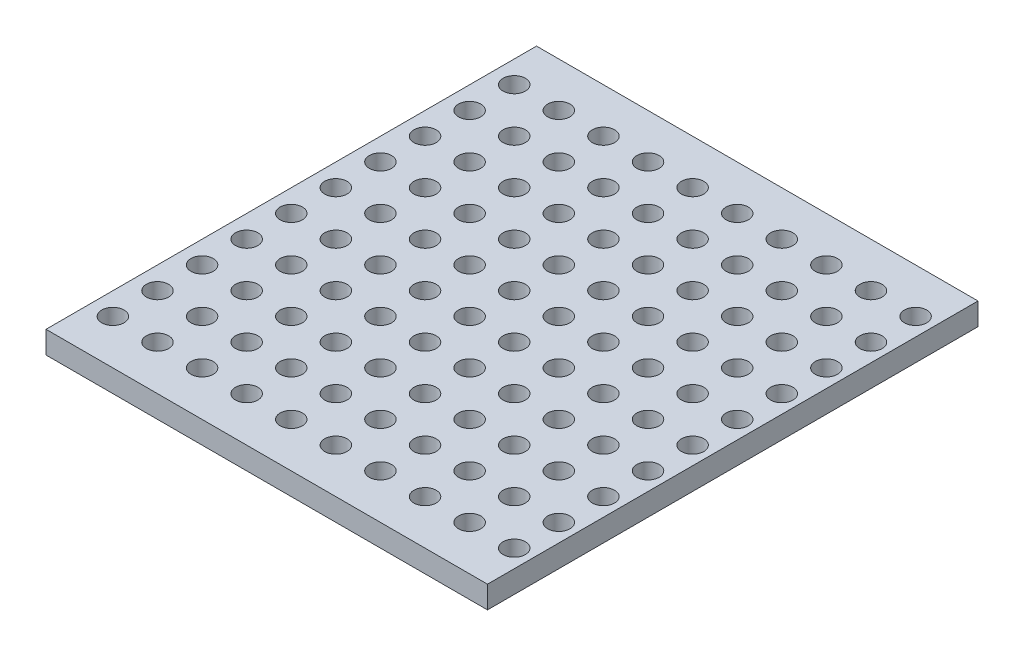
SolidWorks part; units mm, degrees
ref_plane "Alzado" through (0, 0, 0) normal (0, 0, 1) x (1, 0, 0)
ref_plane "Planta" through (0, 0, 0) normal (0, 1, 0) x (1, 0, 0)
ref_plane "Vista lateral" through (0, 0, 0) normal (1, 0, 0) x (0, 0, -1)
sketch "Croquis1" plane through (0, 0, 0) normal (0, 1, 0) x (1, 0, 0)
  line L1 (-9.9, 11) -> (9.9, 11)
  line L2 (-9.9, 11) -> (-9.9, -11)
  line L3 (-9.9, -11) -> (9.9, -11)
  line L4 (9.9, 11) -> (9.9, -11)
  line L5 (-9.9, 11) -> (9.9, -11) construction
  line L6 (-9.9, -11) -> (9.9, 11) construction
  point P0 (0, 0)
  dimension "D1" = 19.8
  dimension "D2" = 22
extrude "Saliente-Extruir1" add sketch "Croquis1" along normal blind 1
sketch "Croquis2" plane through (0, 1, 0) normal (0, 1, 0) x (1, 0, 0)
  line L0 (-9.9, 11) -> (-9.9, -11) construction
  line L1 (9.9, 11) -> (-9.9, 11) construction
  point P0 (-8.9, 9)
  point P3 (-6.9, 9)
  point P6 (-4.9, 9)
  point P7 (-0.9, 9)
  point P8 (1.1, 9)
  point P9 (3.1, 9)
  point P10 (5.1, 9)
  point P11 (7.1, 9)
  point P12 (9.1, 9)
  point P13 (-2.9, 9)
  point P14 (-8.9, 7)
  point P15 (-6.9, 7)
  point P16 (-4.9, 7)
  point P17 (-2.9, 7)
  point P18 (-0.9, 7)
  point P19 (1.1, 7)
  point P20 (3.1, 7)
  point P21 (5.1, 7)
  point P22 (7.1, 7)
  point P23 (9.1, 7)
  point P24 (-8.9, 5)
  point P25 (-6.9, 5)
  point P26 (-4.9, 5)
  point P27 (-2.9, 5)
  point P28 (-0.9, 5)
  point P29 (1.1, 5)
  point P30 (3.1, 5)
  point P31 (5.1, 5)
  point P32 (7.1, 5)
  point P33 (9.1, 5)
  point P34 (-8.9, 3)
  point P35 (-6.9, 3)
  point P36 (-4.9, 3)
  point P37 (-2.9, 3)
  point P38 (-0.9, 3)
  point P39 (1.1, 3)
  point P40 (3.1, 3)
  point P41 (5.1, 3)
  point P42 (7.1, 3)
  point P43 (9.1, 3)
  point P44 (-8.9, 1)
  point P45 (-6.9, 1)
  point P46 (-4.9, 1)
  point P47 (-2.9, 1)
  point P48 (-0.9, 1)
  point P49 (1.1, 1)
  point P50 (3.1, 1)
  point P51 (5.1, 1)
  point P52 (7.1, 1)
  point P53 (9.1, 1)
  point P54 (-8.9, -1)
  point P55 (-6.9, -1)
  point P56 (-4.9, -1)
  point P57 (-2.9, -1)
  point P58 (-0.9, -1)
  point P59 (1.1, -1)
  point P60 (3.1, -1)
  point P61 (5.1, -1)
  point P62 (7.1, -1)
  point P63 (9.1, -1)
  point P64 (-8.9, -3)
  point P65 (-6.9, -3)
  point P66 (-4.9, -3)
  point P67 (-2.9, -3)
  point P68 (-0.9, -3)
  point P69 (1.1, -3)
  point P70 (3.1, -3)
  point P71 (5.1, -3)
  point P72 (7.1, -3)
  point P73 (9.1, -3)
  point P74 (-8.9, -5)
  point P75 (-6.9, -5)
  point P76 (-4.9, -5)
  point P77 (-2.9, -5)
  point P78 (-0.9, -5)
  point P79 (1.1, -5)
  point P80 (3.1, -5)
  point P81 (5.1, -5)
  point P82 (7.1, -5)
  point P83 (9.1, -5)
  point P84 (-8.9, -7)
  point P85 (-6.9, -7)
  point P86 (-4.9, -7)
  point P87 (-2.9, -7)
  point P88 (-0.9, -7)
  point P89 (1.1, -7)
  point P90 (3.1, -7)
  point P91 (5.1, -7)
  point P92 (7.1, -7)
  point P93 (9.1, -7)
  point P94 (-8.9, -9)
  point P95 (-6.9, -9)
  point P96 (-4.9, -9)
  point P97 (-2.9, -9)
  point P98 (-0.9, -9)
  point P99 (1.1, -9)
  point P100 (3.1, -9)
  point P101 (5.1, -9)
  point P102 (7.1, -9)
  point P103 (9.1, -9)
  dimension "D1" = 1
  dimension "D2" = 2
  dimension "D3" = 2
  dimension "D4" = 2
  dimension "D5" = 2
  dimension "D6" = 2
  dimension "D7" = 2
  dimension "D8" = 2
  dimension "D9" = 2
  dimension "D10" = 2
  dimension "D11" = 2
  dimension "D12" = 2
  dimension "D13" = 2
  dimension "D14" = 2
  dimension "D15" = 2
  dimension "D16" = 2
  dimension "D17" = 2
  dimension "D18" = 2
  dimension "D19" = 2
  dimension "D20" = 2
hole_wizard "Diámetro de taladro Ø1.0 (1)1" positions "Croquis3D2" profile "Croquis3" hole size "Ø1.0" standard "DIN"
sketch3d "Croquis3D2"
  point P0 (-8.9, 1, -9)
  point P3 (-6.9, 1, -9)
  point P6 (-4.9, 1, -9)
  point P9 (-2.9, 1, -9)
  point P12 (-0.9, 1, -9)
  point P15 (1.1, 1, -9)
  point P18 (3.1, 1, -9)
  point P21 (5.1, 1, -9)
  point P24 (7.1, 1, -9)
  point P27 (9.1, 1, -9)
  point P30 (-8.9, 1, -7)
  point P33 (-6.9, 1, -7)
  point P36 (-4.9, 1, -7)
  point P39 (-2.9, 1, -7)
  point P42 (-0.9, 1, -7)
  point P45 (1.1, 1, -7)
  point P48 (3.1, 1, -7)
  point P51 (5.1, 1, -7)
  point P54 (7.1, 1, -7)
  point P57 (9.1, 1, -7)
  point P60 (9.1, 1, -5)
  point P63 (7.1, 1, -5)
  point P66 (5.1, 1, -5)
  point P69 (3.1, 1, -5)
  point P72 (1.1, 1, -5)
  point P75 (-0.9, 1, -5)
  point P78 (-2.9, 1, -5)
  point P81 (-4.9, 1, -5)
  point P84 (-6.9, 1, -5)
  point P87 (-8.9, 1, -5)
  point P90 (-8.9, 1, -3)
  point P93 (-6.9, 1, -3)
  point P96 (-4.9, 1, -3)
  point P99 (-2.9, 1, -3)
  point P102 (-0.9, 1, -3)
  point P105 (1.1, 1, -3)
  point P108 (3.1, 1, -3)
  point P111 (5.1, 1, -3)
  point P114 (7.1, 1, -3)
  point P117 (9.1, 1, -3)
  point P120 (9.1, 1, -1)
  point P123 (7.1, 1, -1)
  point P126 (5.1, 1, -1)
  point P129 (3.1, 1, -1)
  point P132 (1.1, 1, -1)
  point P135 (-0.9, 1, -1)
  point P138 (-2.9, 1, -1)
  point P141 (-4.9, 1, -1)
  point P144 (-6.9, 1, -1)
  point P147 (-8.9, 1, -1)
  point P150 (-8.9, 1, 1)
  point P153 (-6.9, 1, 1)
  point P156 (-4.9, 1, 1)
  point P159 (-2.9, 1, 1)
  point P162 (-0.9, 1, 1)
  point P165 (1.1, 1, 1)
  point P168 (3.1, 1, 1)
  point P171 (5.1, 1, 1)
  point P174 (7.1, 1, 1)
  point P177 (9.1, 1, 1)
  point P180 (9.1, 1, 3)
  point P183 (7.1, 1, 3)
  point P186 (5.1, 1, 3)
  point P189 (3.1, 1, 3)
  point P192 (1.1, 1, 3)
  point P195 (-0.9, 1, 3)
  point P198 (-2.9, 1, 3)
  point P201 (-4.9, 1, 3)
  point P204 (-6.9, 1, 3)
  point P207 (-8.9, 1, 3)
  point P210 (-8.9, 1, 5)
  point P213 (-6.9, 1, 5)
  point P216 (-4.9, 1, 5)
  point P219 (-2.9, 1, 5)
  point P222 (-0.9, 1, 5)
  point P225 (1.1, 1, 5)
  point P228 (3.1, 1, 5)
  point P231 (5.1, 1, 5)
  point P234 (7.1, 1, 5)
  point P237 (9.1, 1, 5)
  point P240 (9.1, 1, 7)
  point P243 (7.1, 1, 7)
  point P246 (5.1, 1, 7)
  point P249 (3.1, 1, 7)
  point P252 (1.1, 1, 7)
  point P255 (-0.9, 1, 7)
  point P258 (-2.9, 1, 7)
  point P261 (-4.9, 1, 7)
  point P264 (-6.9, 1, 7)
  point P267 (-8.9, 1, 7)
  point P270 (-8.9, 1, 9)
  point P273 (-6.9, 1, 9)
  point P276 (-4.9, 1, 9)
  point P279 (-2.9, 1, 9)
  point P282 (-0.9, 1, 9)
  point P285 (1.1, 1, 9)
  point P288 (3.1, 1, 9)
  point P291 (5.1, 1, 9)
  point P294 (7.1, 1, 9)
  point P297 (9.1, 1, 9)
sketch "Croquis3" plane through (-8.9, 1, -9) normal (1, 0, 0) x (0, 0, 1)
  line L0 (0, 0) -> (0, 12.3004)
  line L1 (0, 12.3004) -> (0.5, 12)
  line L2 (0.5, 12) -> (0.5, 0)
  line L5 (0.5, 0) -> (0, 0)
  line L10 (0, 12.3004) -> (-0.5, 12) construction
  line L11 (0, -6.35) -> (0, 107.95) construction
  dimension "Diámetro de taladro" = 1
  dimension "Profundidad de taladro" = 12
  dimension "Ángulo de perforador" = 118
